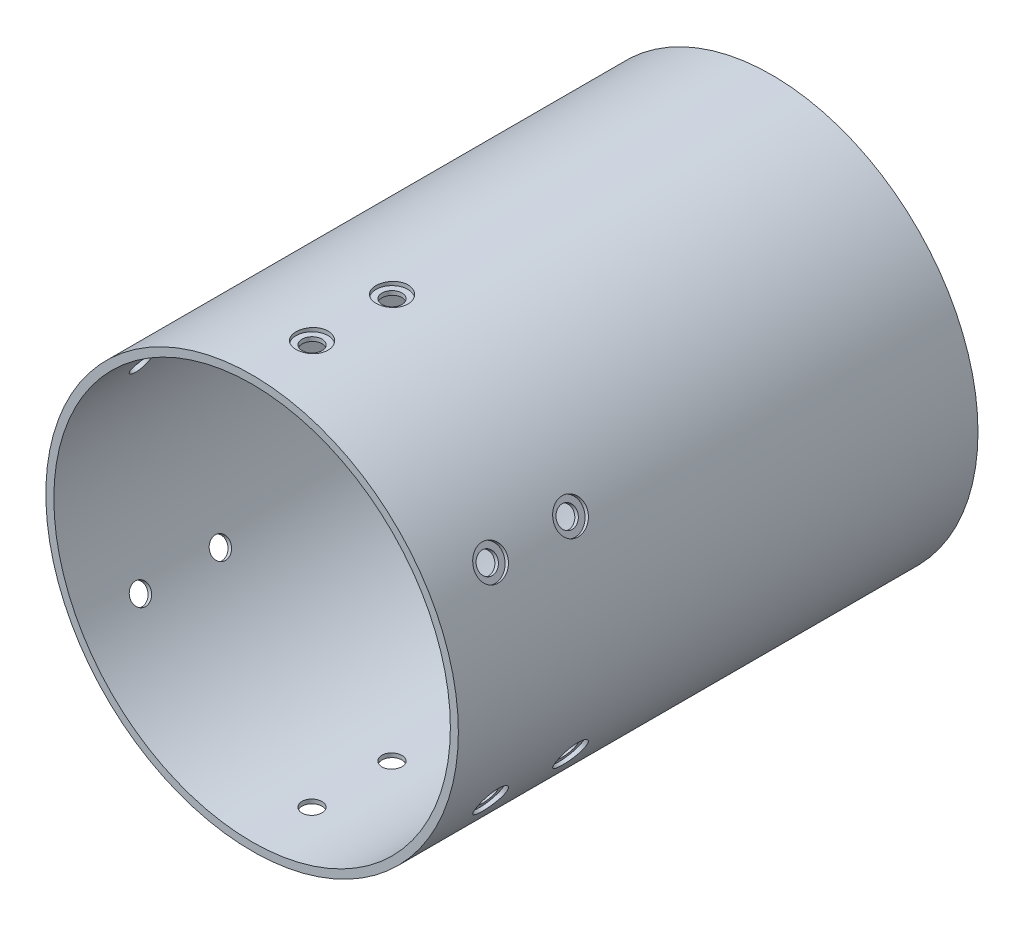
SolidWorks part; units mm, degrees
ref_plane "Front Plane" through (0, 0, 0) normal (0, 0, 1) x (1, 0, 0)
ref_plane "Top Plane" through (0, 0, 0) normal (0, 1, 0) x (1, 0, 0)
ref_plane "Right Plane" through (0, 0, 0) normal (1, 0, 0) x (0, 0, -1)
sketch "Sketch1" plane through (0, 0, 0) normal (0, 0, 1) x (1, 0, 0)
  circle A0 centre (0, 0) radius 49.6
  circle A1 centre (0, 0) radius 51.6
  dimension "D1" = 99.2
  dimension "D2" = 103.2
extrude "Boss-Extrude1" add sketch "Sketch1" along normal blind 130
ref_plane "Plane1" through (0, -51.6, 0) normal (0, -1, 0) x (-1, 0, 0)
sketch "Sketch2" plane through (0, -51.6, 0) normal (0, -1, 0) x (-1, 0, 0)
  line L0 (-51.6, -130) -> (51.6, -130) construction
  circle A0 centre (0, -95) radius 4
  circle A1 centre (0, -115) radius 4
  dimension "D1" = 8
  dimension "D2" = 8
  dimension "D3" = 15
  dimension "D4" = 35
extrude "Cut-Extrude1" cut sketch "Sketch2" against normal blind 1
sketch "Sketch3" plane through (0, -51.6, 0) normal (0, -1, 0) x (-1, 0, 0)
  circle A0 centre (0, -95) radius 2.5
  circle A1 centre (0, -115) radius 2.5
  dimension "D1" = 5
  dimension "D2" = 5
extrude "Cut-Extrude2" cut sketch "Sketch3" against normal blind 3
pattern_circular "CirPattern1" count 6 over 360 about axis through (0, 0, 0) along (0, 0, 1) of "Cut-Extrude2", "Cut-Extrude1"
